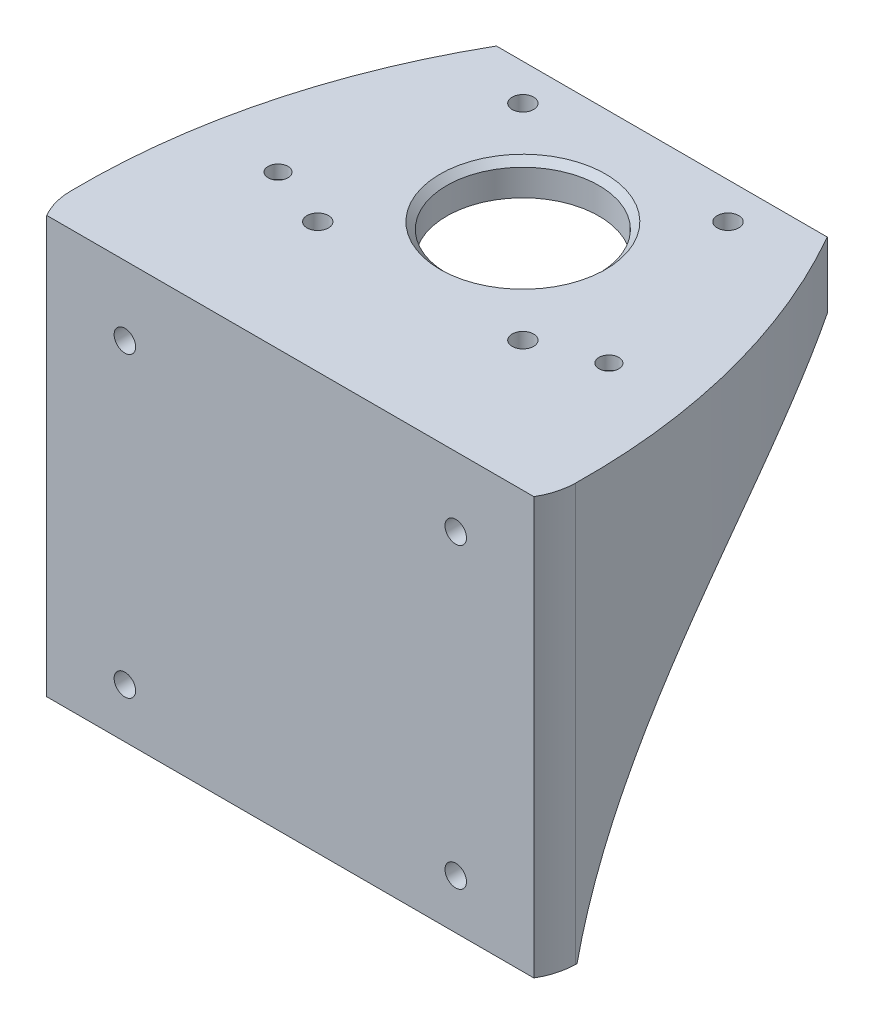
SolidWorks part; units mm, degrees
ref_plane "Plan de face" through (0, 0, 0) normal (0, 0, 1) x (1, 0, 0)
ref_plane "Plan de dessus" through (0, 0, 0) normal (0, 1, 0) x (1, 0, 0)
ref_plane "Plan de droite" through (0, 0, 0) normal (1, 0, 0) x (0, 0, -1)
sketch "Esquisse1" plane through (0, 0, 0) normal (0, 0, 1) x (1, 0, 0)
  line L1 (0, 0) -> (62, 0)
  line L2 (0, 0) -> (0, 60)
  line L3 (0, 60) -> (62, 60)
  line L4 (62, 0) -> (62, 60)
  dimension "D1" = 62
  dimension "D2" = 60
extrude "Boss.-Extru.1" add sketch "Esquisse1" along normal blind 10
sketch "Esquisse3" plane through (0, 0, 10) normal (0, 0, 1) x (1, 0, 0)
  line L0 (0, 60) -> (62, 0) construction
  line L1 (62, 0) -> (0, 0) construction
  line L2 (0, 0) -> (62, 60) construction
  line L3 (62, 0) -> (62, 60) construction
  line L4 (62, 60) -> (0, 60) construction
  line L6 (0, 60) -> (0, 0) construction
  circle A0 centre (6, 52.5) radius 5
  circle A1 centre (56, 7.5) radius 5
  circle A2 centre (6, 7.5) radius 5
  circle A3 centre (56, 52.5) radius 5
  dimension "D1" = 10
  dimension "D4" = 10
  dimension "D8" = 10
  dimension "D9" = 10
  dimension "D2" = 7.5
  dimension "D3" = 7.5
  dimension "D5" = 6
  dimension "D6" = 50
  dimension "D7" = 50
  dimension "D10" = 6
  dimension "D11" = 7.5
  dimension "D12" = 7.5
extrude "Boss.-Extru.2" add sketch "Esquisse3" along normal blind 5
sketch "Esquisse4" plane through (0, 0, 15) normal (0, 0, 1) x (1, 0, 0)
  circle A0 centre (6, 52.5) radius 3.5
  circle A1 centre (56, 52.5) radius 3.5
  circle A2 centre (56, 7.5) radius 3.5
  circle A3 centre (6, 7.5) radius 3.5
  dimension "D1" = 7
  dimension "D2" = 7
  dimension "D3" = 7
  dimension "D4" = 7
extrude "Boss.-Extru.3" add sketch "Esquisse4" along normal blind 2
sketch "Esquisse5" plane through (0, 0, 17) normal (0, 0, 1) x (1, 0, 0)
  circle A0 centre (6, 52.5) radius 1.625
  circle A1 centre (56, 52.5) radius 1.625
  circle A2 centre (56, 7.5) radius 1.625
  circle A3 centre (6, 7.5) radius 1.625
  dimension "D1" = 3.25
  dimension "D2" = 3.25
  dimension "D3" = 3.25
  dimension "D4" = 3.25
extrude "Enlèv. mat.-Extru.2" cut sketch "Esquisse5" against normal through all
sketch "Esquisse7" plane through (0, 60, 0) normal (0, 1, 0) x (1, 0, 0)
  line L1 (0, 0) -> (0, -10)
  line L2 (0, -10) -> (62, -10)
  line L4 (6, 51) -> (56, 51)
  line L6 (62, -10) -> (62, 0)
  line L17 (62, -10) -> (62, 0) construction
  arc A4 (62, 0) -> (56, 51) centre (-67.5663, 10.6098) ccw
  arc A5 (0, 0) -> (6, 51) centre (129.5663, 10.6098) cw
  point P20 (62, -5)
  dimension "D4" = 6
  dimension "D3" = 130
  dimension "D9" = 130
  dimension "D2" = 6
  dimension "D1" = 61
extrude "Boss.-Extru.4" add sketch "Esquisse7" along normal mid plane 6
sketch "Esquisse9" plane through (0, 63, 0) normal (0, 1, 0) x (1, 0, 0)
  line L0 (0, -10) -> (62, -10) construction
  line L1 (0, 0) -> (0, -10) construction
  line L2 (62, -10) -> (62, 0) construction
  circle A0 centre (31, 30) radius 11.5
  circle A1 centre (46.5, 14.5) radius 1.625
  circle A2 centre (15.5, 14.5) radius 1.625
  circle A3 centre (15.5, 45.5) radius 1.625
  circle A4 centre (15.5, 45.5) radius 1.625
  circle A5 centre (46.5, 45.5) radius 1.625
  circle A6 centre (56, 18) radius 1.5
  circle A7 centre (6, 18) radius 1.5
  point P21 (62, -5)
  dimension "D3" = 3.25
  dimension "D4" = 3.25
  dimension "D5" = 3.25
  dimension "D6" = 3.25
  dimension "D11" = 31
  dimension "D9" = 3.25
  dimension "D14" = 23
  dimension "D15" = 50
  dimension "D16" = 3
  dimension "D17" = 3
  dimension "D1" = 40
  dimension "D2" = 31
  dimension "D7" = 31
  dimension "D8" = 31
  dimension "D10" = 31
  dimension "D12" = 15.5
  dimension "D13" = 15.5
  dimension "D18" = 6
  dimension "D19" = 12
extrude "Enlèv. mat.-Extru.4" cut sketch "Esquisse9" against normal blind 10 contours A0 | A7 | A2 | A1 | A6 | A5 | A3
ref_plane "Plan1" through (0, 0, 0) normal (-0.9932, 0, -0.1168) x (-0.1168, 0, 0.9932)
sketch "Esquisse14" plane through (0, 63, 0) normal (0, 1, 0) x (1, 0, 0)
  line L0 (0, 0) -> (0, -10)
  line L1 (0, -10) -> (-6.9282, -6)
  line L3 (56, 51) -> (6, 51) construction
  line L4 (11.0445, 51) -> (6, 51)
  arc A0 (11.0445, 51) -> (0, 0) centre (129.9919, -1.4549) ccw
  arc A2 (6, 51) -> (-6.9282, -6) centre (92.8016, 1.3464) ccw
  dimension "D1" = 100
  dimension "D2" = 8
  dimension "D3" = 60
extrude "Boss.-Extru.6" add sketch "Esquisse14" against normal blind 63
ref_plane "Plan2" through (31, 0, 0) normal (1, 0, 0) x (0, 0, -1)
mirror "Symétrie1" about plane through (31, 0, 0) normal (1, 0, 0) of "Boss.-Extru.6"
sketch "Esquisse16" plane through (0, 57, 0) normal (0, -1, 0) x (1, 0, 0)
  line L1 (10.0415, -18) -> (8.0207, -14.5)
  line L2 (8.0207, -14.5) -> (3.9793, -14.5)
  line L3 (3.9793, -14.5) -> (1.9585, -18)
  line L4 (1.9585, -18) -> (3.9793, -21.5)
  line L5 (3.9793, -21.5) -> (8.0207, -21.5)
  line L6 (8.0207, -21.5) -> (10.0415, -18)
  line L7 (60.0415, -18) -> (58.0207, -14.5)
  line L8 (58.0207, -14.5) -> (53.9793, -14.5)
  line L9 (53.9793, -14.5) -> (51.9585, -18)
  line L10 (51.9585, -18) -> (53.9793, -21.5)
  line L11 (53.9793, -21.5) -> (58.0207, -21.5)
  line L12 (58.0207, -21.5) -> (60.0415, -18)
  circle A0 centre (6, -18) radius 3.5 construction
  circle A1 centre (56, -18) radius 3.5 construction
  dimension "D1" = 7
  dimension "D2" = 7
extrude "Enlèv. mat.-Extru.6" cut sketch "Esquisse16" against normal blind 4
sketch "Esquisse18" plane through (0, 0, 0) normal (1, 0, 0) x (0, 0, -1)
  line L1 (-6, 0) -> (51, 0) construction
  line L2 (51, 63) -> (51, 0) construction
  line L3 (51, 63) -> (-6, 63) construction
  line L4 (51, 53) -> (51, 0)
  line L5 (51, 0) -> (0, 0)
  arc A0 (51, 53) -> (0, 0) centre (68.4179, -14.7984) ccw
  dimension "D3" = 70
  dimension "D1" = 10
  dimension "D2" = 10
extrude "Enlèv. mat.-Extru.7" cut sketch "Esquisse18" along normal mid plane 204
sketch "Esquisse19" plane through (0, 57, 0) normal (0, -1, 0) x (1, 0, 0)
  line L1 (10, -51) -> (52, -51)
  line L2 (10, -51) -> (10, -9)
  line L3 (10, -9) -> (52, -9)
  line L4 (52, -51) -> (52, -9)
  line L5 (10, -51) -> (52, -9) construction
  line L6 (10, -9) -> (52, -51) construction
  point P0 (31, -30)
  dimension "D1" = 42
  dimension "D2" = 42
extrude "Enlèv. mat.-Extru.8" cut sketch "Esquisse19" against normal blind 1 and the other way blind 23
chamfer "Chanfrein1" distance 1 angle 45 1 edges at (31, 63, -18.5)
fillet "Congé1" radius 10 2 edges at (-6.9282, 31.5, 6) (68.9282, 31.5, 6)
sketch "Esquisse20" plane through (0, 63, 0) normal (0, 1, 0) x (1, 0, 0)
  line L1 (67.8076, -5.1453) -> (-10.8729, -5.1453)
  line L2 (67.8076, -5.1453) -> (67.8076, -22.5809)
  line L3 (67.8076, -22.5809) -> (-10.8729, -22.5809)
  line L4 (-10.8729, -5.1453) -> (-10.8729, -22.5809)
  arc A2 (64.1872, -8.7372) -> (69.1859, -0.2351) centre (59.1872, -0.077) ccw construction
extrude "Enlèv. mat.-Extru.9" cut sketch "Esquisse20" against normal through all
